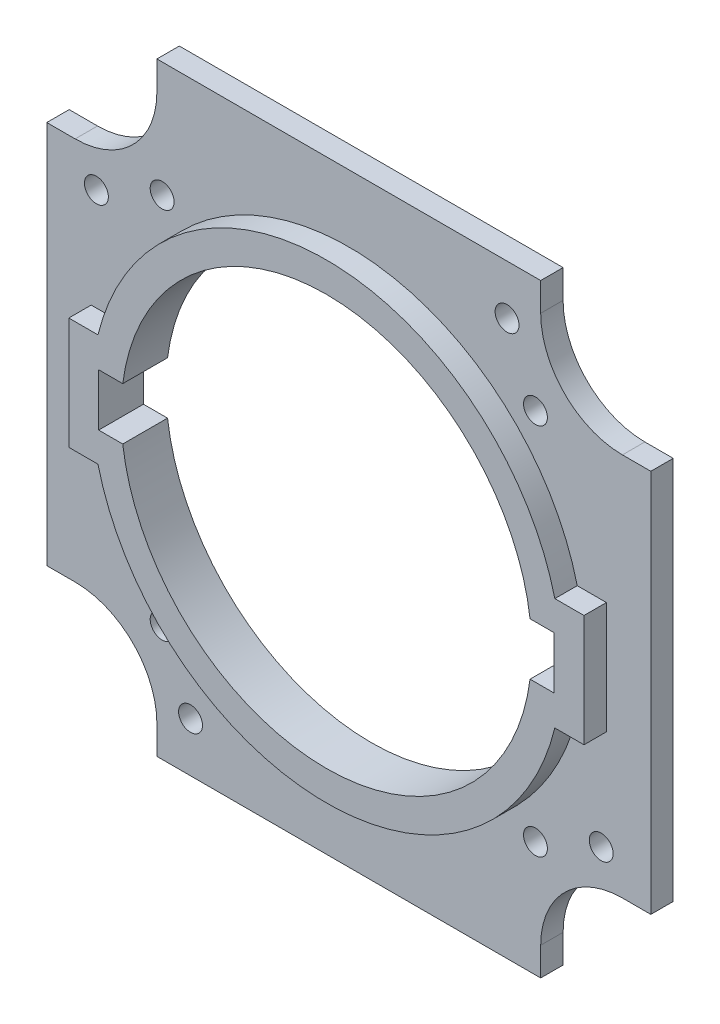
SolidWorks part; units mm, degrees
ref_plane "前视基准面" through (0, 0, 0) normal (0, 0, 1) x (1, 0, 0)
ref_plane "上视基准面" through (0, 0, 0) normal (0, 1, 0) x (1, 0, 0)
ref_plane "右视基准面" through (0, 0, 0) normal (1, 0, 0) x (0, 0, -1)
sketch "草图1" plane through (0, 0, 0) normal (0, 0, 1) x (1, 0, 0)
  line L0 (-27.5, 43.25) -> (27.5, 43.25)
  line L1 (-43.25, 27.5) -> (-43.25, 49.7664) construction
  line L5 (-42.25, 28.5) -> (-36.65, 28.5)
  line L6 (-28.5, 42.25) -> (-28.5, 36.65)
  line L7 (43.25, 27.5) -> (43.25, -27.5)
  line L8 (28.5, 42.25) -> (28.5, 36.65)
  line L9 (42.25, 28.5) -> (36.65, 28.5)
  line L10 (27.5, -43.25) -> (-27.5, -43.25)
  line L11 (42.25, -28.5) -> (36.65, -28.5)
  line L12 (28.5, -42.25) -> (28.5, -36.65)
  line L13 (-43.25, -27.5) -> (-43.25, 27.5)
  line L14 (-28.5, -42.25) -> (-28.5, -36.65)
  line L15 (-42.25, -28.5) -> (-36.65, -28.5)
  arc A0 (-27.5, 43.25) -> (-28.5, 42.25) centre (-27.5, 42.25) ccw
  arc A2 (-42.25, 28.5) -> (-43.25, 27.5) centre (-42.25, 27.5) ccw
  arc A12 (-28.5, 36.65) -> (-36.65, 28.5) centre (-36.65, 36.65) cw
  arc A13 (43.25, 27.5) -> (42.25, 28.5) centre (42.25, 27.5) ccw
  arc A14 (28.5, 42.25) -> (27.5, 43.25) centre (27.5, 42.25) ccw
  arc A15 (36.65, 28.5) -> (28.5, 36.65) centre (36.65, 36.65) cw
  arc A16 (27.5, -43.25) -> (28.5, -42.25) centre (27.5, -42.25) ccw
  arc A17 (42.25, -28.5) -> (43.25, -27.5) centre (42.25, -27.5) ccw
  arc A18 (28.5, -36.65) -> (36.65, -28.5) centre (36.65, -36.65) cw
  arc A19 (-43.25, -27.5) -> (-42.25, -28.5) centre (-42.25, -27.5) ccw
  arc A20 (-28.5, -42.25) -> (-27.5, -43.25) centre (-27.5, -42.25) ccw
  arc A21 (-36.65, -28.5) -> (-28.5, -36.65) centre (-36.65, -36.65) cw
  point P8 (0, 43.25)
  point P46 (0, 0)
  dimension "D2" = 1
  dimension "D1" = 43.25
  dimension "D3" = 43.25
  dimension "D4" = 55
  dimension "D5" = 5.6
extrude "凸台-拉伸1" add sketch "草图1" along normal blind 3
sketch "草图6" plane through (0, 0, 3) normal (0, 0, 1) x (1, 0, 0)
  line L0 (-25.7, 40.45) -> (-25.7, 36.65)
  line L1 (-36.65, 25.7) -> (-40.45, 25.7)
  line L2 (-40.45, 25.7) -> (-40.45, -25.7)
  line L3 (-40.45, -25.7) -> (-36.65, -25.7)
  line L4 (-25.7, -36.65) -> (-25.7, -40.45)
  line L6 (-25.7, -40.45) -> (25.7, -40.45)
  line L7 (25.7, -40.45) -> (25.7, -36.65)
  line L12 (36.65, -25.7) -> (40.45, -25.7)
  line L13 (40.45, -25.7) -> (40.45, 25.7)
  line L14 (40.45, 25.7) -> (36.65, 25.7)
  line L15 (25.7, 36.65) -> (25.7, 40.45)
  line L16 (25.7, 40.45) -> (-25.7, 40.45)
  line L17 (-28.5, 42.25) -> (-28.5, 36.65)
  line L18 (-36.65, 28.5) -> (-42.25, 28.5)
  line L19 (-43.25, 27.5) -> (-43.25, -27.5)
  line L20 (-42.25, -28.5) -> (-36.65, -28.5)
  line L21 (-28.5, -36.65) -> (-28.5, -42.25)
  line L22 (-27.5, -43.25) -> (27.5, -43.25)
  line L23 (28.5, -42.25) -> (28.5, -36.65)
  line L24 (36.65, -28.5) -> (42.25, -28.5)
  line L25 (43.25, -27.5) -> (43.25, 27.5)
  line L26 (42.25, 28.5) -> (36.65, 28.5)
  line L28 (28.5, 36.65) -> (28.5, 42.25)
  line L30 (27.5, 43.25) -> (-27.5, 43.25)
  line L32 (-28.5, 42.25) -> (-28.5, 36.65)
  line L34 (-36.65, 28.5) -> (-42.25, 28.5)
  line L36 (-43.25, 27.5) -> (-43.25, -27.5)
  line L38 (-42.25, -28.5) -> (-36.65, -28.5)
  line L40 (-28.5, -36.65) -> (-28.5, -42.25)
  line L42 (-27.5, -43.25) -> (27.5, -43.25)
  line L44 (28.5, -42.25) -> (28.5, -36.65)
  line L46 (36.65, -28.5) -> (42.25, -28.5)
  line L47 (43.25, -27.5) -> (43.25, 27.5)
  line L48 (42.25, 28.5) -> (36.65, 28.5)
  line L49 (28.5, 36.65) -> (28.5, 42.25)
  line L50 (27.5, 43.25) -> (-27.5, 43.25)
  arc A0 (-25.7, 40.45) -> (-25.7, 40.45) centre (-25.7, 40.45) ccw
  arc A1 (-36.65, 25.7) -> (-25.7, 36.65) centre (-36.65, 36.65) ccw
  arc A2 (-40.45, 25.7) -> (-40.45, 25.7) centre (-40.45, 25.7) ccw
  arc A3 (-40.45, -25.7) -> (-40.45, -25.7) centre (-40.45, -25.7) ccw
  arc A4 (-25.7, -36.65) -> (-36.65, -25.7) centre (-36.65, -36.65) ccw
  arc A5 (-25.7, -40.45) -> (-25.7, -40.45) centre (-25.7, -40.45) ccw
  arc A6 (25.7, -40.45) -> (25.7, -40.45) centre (25.7, -40.45) ccw
  arc A7 (36.65, -25.7) -> (25.7, -36.65) centre (36.65, -36.65) ccw
  arc A8 (40.45, -25.7) -> (40.45, -25.7) centre (40.45, -25.7) ccw
  arc A9 (40.45, 25.7) -> (40.45, 25.7) centre (40.45, 25.7) ccw
  arc A10 (25.7, 36.65) -> (36.65, 25.7) centre (36.65, 36.65) ccw
  arc A11 (25.7, 40.45) -> (25.7, 40.45) centre (25.7, 40.45) ccw
  arc A12 (-27.5, 43.25) -> (-28.5, 42.25) centre (-27.5, 42.25) ccw
  arc A13 (-36.65, 28.5) -> (-28.5, 36.65) centre (-36.65, 36.65) ccw
  arc A14 (-42.25, 28.5) -> (-43.25, 27.5) centre (-42.25, 27.5) ccw
  arc A16 (-43.25, -27.5) -> (-42.25, -28.5) centre (-42.25, -27.5) ccw
  arc A18 (-28.5, -36.65) -> (-36.65, -28.5) centre (-36.65, -36.65) ccw
  arc A20 (-28.5, -42.25) -> (-27.5, -43.25) centre (-27.5, -42.25) ccw
  arc A22 (27.5, -43.25) -> (28.5, -42.25) centre (27.5, -42.25) ccw
  arc A36 (36.65, -28.5) -> (28.5, -36.65) centre (36.65, -36.65) ccw
  arc A37 (42.25, -28.5) -> (43.25, -27.5) centre (42.25, -27.5) ccw
  arc A38 (43.25, 27.5) -> (42.25, 28.5) centre (42.25, 27.5) ccw
  arc A39 (28.5, 36.65) -> (36.65, 28.5) centre (36.65, 36.65) ccw
  arc A40 (28.5, 42.25) -> (27.5, 43.25) centre (27.5, 42.25) ccw
  arc A41 (-27.5, 43.25) -> (-28.5, 42.25) centre (-27.5, 42.25) ccw
  arc A42 (-36.65, 28.5) -> (-28.5, 36.65) centre (-36.65, 36.65) ccw
  arc A43 (-42.25, 28.5) -> (-43.25, 27.5) centre (-42.25, 27.5) ccw
  arc A44 (-43.25, -27.5) -> (-42.25, -28.5) centre (-42.25, -27.5) ccw
  arc A45 (-28.5, -36.65) -> (-36.65, -28.5) centre (-36.65, -36.65) ccw
  arc A46 (-28.5, -42.25) -> (-27.5, -43.25) centre (-27.5, -42.25) ccw
  arc A47 (27.5, -43.25) -> (28.5, -42.25) centre (27.5, -42.25) ccw
  arc A48 (36.65, -28.5) -> (28.5, -36.65) centre (36.65, -36.65) ccw
  arc A49 (42.25, -28.5) -> (43.25, -27.5) centre (42.25, -27.5) ccw
  arc A50 (43.25, 27.5) -> (42.25, 28.5) centre (42.25, 27.5) ccw
  arc A51 (28.5, 36.65) -> (36.65, 28.5) centre (36.65, 36.65) ccw
  arc A52 (28.5, 42.25) -> (27.5, 43.25) centre (27.5, 42.25) ccw
  dimension "D1" = 0
  dimension "D2" = 2.8
extrude "切除-拉伸2" cut sketch "草图6" against normal through all
sketch "草图2" plane through (0, 0, 3) normal (0, 0, 1) x (1, 0, 0)
  line L0 (-21.1948, -33.8052) -> (-33.8052, 21.1948) construction
  line L1 (-21.1948, -33.8052) -> (33.8052, -21.1948) construction
  line L2 (-33.8052, 21.1948) -> (21.1948, 33.8052) construction
  line L3 (33.8052, -21.1948) -> (21.1948, 33.8052) construction
  line L4 (-21.1948, -33.8052) -> (21.1948, 33.8052) construction
  line L5 (-33.8052, 21.1948) -> (33.8052, -21.1948) construction
  circle A18 centre (-33.8052, 21.1948) radius 1.6
  circle A19 centre (21.1948, 33.8052) radius 1.6
  circle A20 centre (33.8052, -21.1948) radius 1.6
  circle A21 centre (-21.1948, -33.8052) radius 1.6
  point P1 (0, 0)
  point P16 (0, 0)
  point P30 (0, 0)
  point P47 (0, 0)
  dimension "D3" = 3.2
  dimension "D1" = 79.8
  dimension "D2" = 55
sketch "草图7" plane through (0, 0, 3) normal (0, 0, 1) x (1, 0, 0)
  line L1 (-25, -25) -> (25, -25) construction
  line L2 (-25, -25) -> (-25, 25) construction
  line L3 (-25, 25) -> (25, 25) construction
  line L4 (25, -25) -> (25, 25) construction
  line L5 (-25, -25) -> (25, 25) construction
  line L6 (-25, 25) -> (25, -25) construction
  circle A0 centre (-25, 25) radius 1.6
  circle A1 centre (25, 25) radius 1.6
  circle A2 centre (25, -25) radius 1.6
  circle A3 centre (-25, -25) radius 1.6
  circle A4 centre (0, 0) radius 27.5
  point P0 (0, 0)
  dimension "D2" = 3.2
  dimension "D3" = 55
  dimension "D1" = 50
extrude "切除-拉伸3" cut sketch "草图7" against normal through all
extrude "切除-拉伸4" cut sketch "草图2" against normal through all
sketch "草图8" plane through (0, 0, 3) normal (0, 0, 1) x (1, 0, 0)
  line L1 (-30.5, -3.5) -> (30.5, -3.5)
  line L2 (-30.5, -3.5) -> (-30.5, 3.5)
  line L3 (-30.5, 3.5) -> (30.5, 3.5)
  line L4 (30.5, -3.5) -> (30.5, 3.5)
  line L5 (-30.5, -3.5) -> (30.5, 3.5) construction
  line L6 (-30.5, 3.5) -> (30.5, -3.5) construction
  point P0 (0, 0)
  dimension "D1" = 61
  dimension "D2" = 7
extrude "切除-拉伸5" cut sketch "草图8" against normal through all
sketch "草图9" plane through (0, 0, 3) normal (0, 0, 1) x (1, 0, 0)
  line L0 (-30.5, -3.5) -> (-27.2764, -3.5) construction
  line L1 (-27.2764, 3.5) -> (-30.5, 3.5) construction
  line L2 (-30.5, 3.5) -> (-30.5, -3.5) construction
  line L3 (30.5, -3.5) -> (30.5, 3.5) construction
  line L4 (30.5, 3.5) -> (27.2764, 3.5) construction
  line L5 (27.2764, -3.5) -> (30.5, -3.5) construction
  line L6 (-30.5, -3.5) -> (-27.2764, -3.5)
  line L7 (-27.2764, 3.5) -> (-30.5, 3.5)
  line L8 (-30.5, 3.5) -> (-30.5, -3.5)
  line L9 (30.5, -3.5) -> (30.5, 3.5)
  line L10 (30.5, 3.5) -> (27.2764, 3.5)
  line L11 (27.2764, -3.5) -> (30.5, -3.5)
  line L12 (-34.5, -7.5) -> (-30.5941, -7.5)
  line L13 (30.5941, -7.5) -> (34.5, -7.5)
  line L14 (34.5, -7.5) -> (34.5, 7.5)
  line L15 (34.5, 7.5) -> (30.5941, 7.5)
  line L16 (-30.5941, 7.5) -> (-34.5, 7.5)
  line L17 (-34.5, 7.5) -> (-34.5, -7.5)
  arc A0 (-27.2764, -3.5) -> (27.2764, -3.5) centre (0, 0) ccw construction
  arc A1 (27.2764, 3.5) -> (-27.2764, 3.5) centre (0, 0) ccw construction
  arc A2 (-27.2764, -3.5) -> (27.2764, -3.5) centre (0, 0) ccw
  arc A3 (27.2764, 3.5) -> (-27.2764, 3.5) centre (0, 0) ccw
  arc A4 (-30.5941, -7.5) -> (30.5941, -7.5) centre (0, 0) ccw
  arc A5 (30.5941, 7.5) -> (-30.5941, 7.5) centre (0, 0) ccw
  dimension "D1" = 4
extrude "凸台-拉伸2" add sketch "草图9" along normal blind 3
